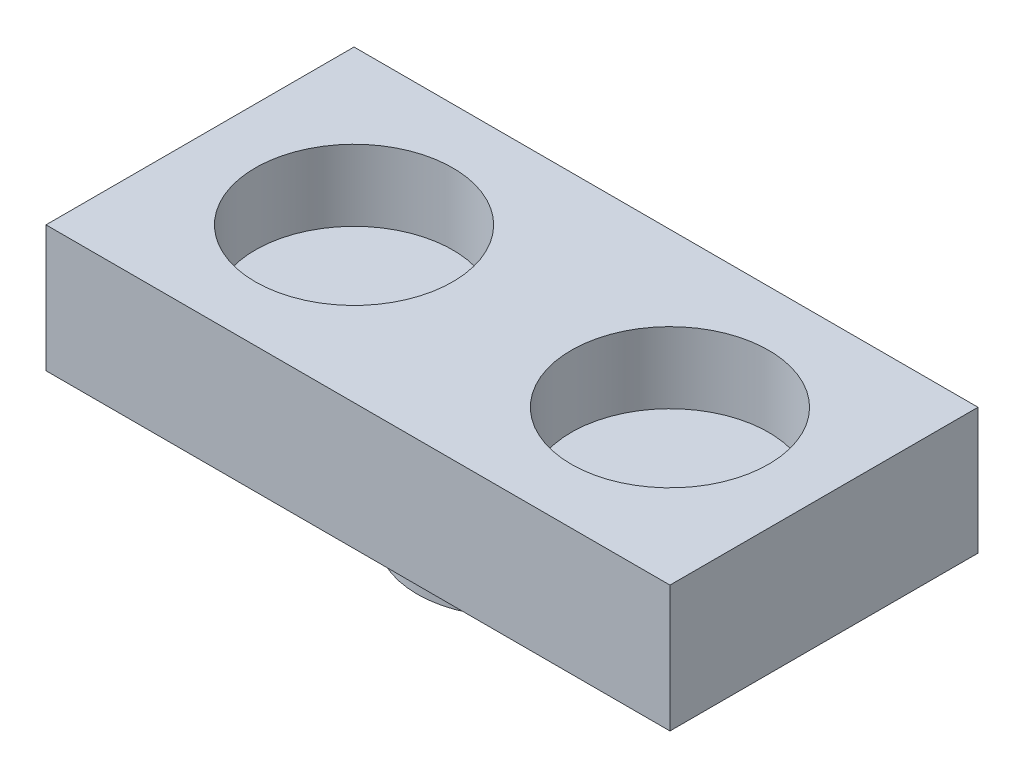
SolidWorks part; units mm, degrees
ref_plane "Спереди" through (0, 0, 0) normal (0, 0, 1) x (1, 0, 0)
ref_plane "Сверху" through (0, 0, 0) normal (0, 1, 0) x (1, 0, 0)
ref_plane "Справа" through (0, 0, 0) normal (1, 0, 0) x (0, 0, -1)
sketch "Эскиз1" plane through (0, 0, 0) normal (0, 1, 0) x (1, 0, 0)
  line L1 (7.9, -3.9) -> (-7.9, -3.9)
  line L2 (7.9, -3.9) -> (7.9, 3.9)
  line L3 (7.9, 3.9) -> (-7.9, 3.9)
  line L4 (-7.9, -3.9) -> (-7.9, 3.9)
  line L5 (7.9, -3.9) -> (-7.9, 3.9) construction
  line L6 (7.9, 3.9) -> (-7.9, -3.9) construction
  circle A0 centre (0, 0) radius 2.4
  point P0 (0, 0)
  dimension "D3" = 4.8
  dimension "D1" = 15.8
  dimension "D2" = 7.8
extrude "Бобышка-Вытянуть1" add sketch "Эскиз1" along normal blind 3.2 contours A0 | L4 L1 L2 L3 A0
sketch "Эскиз2" plane through (0, 0, 0) normal (0, 1, 0) x (1, 0, 0)
  circle A0 centre (0, 0) radius 2.4
  circle A1 centre (0, 0) radius 1.6
  dimension "D1" = 4.8
  dimension "D2" = 3.2
extrude "Бобышка-Вытянуть2" add sketch "Эскиз2" against normal blind 1.7
sketch "Эскиз3" plane through (0, 3.2, 0) normal (0, 1, 0) x (1, 0, 0)
  line L0 (-7.9, -3.9) -> (-7.9, 3.9) construction
  line L1 (7.9, 3.9) -> (-7.9, 3.9) construction
  line L2 (7.9, -3.9) -> (7.9, 3.9) construction
  circle A0 centre (-4, 0) radius 2.5
  circle A1 centre (4, 0) radius 2.5
  dimension "D1" = 3.9
  dimension "D2" = 3.9
  dimension "D3" = 3.9
extrude "Вырез-Вытянуть2" cut sketch "Эскиз3" against normal blind 1.8 contours A0 | A1
